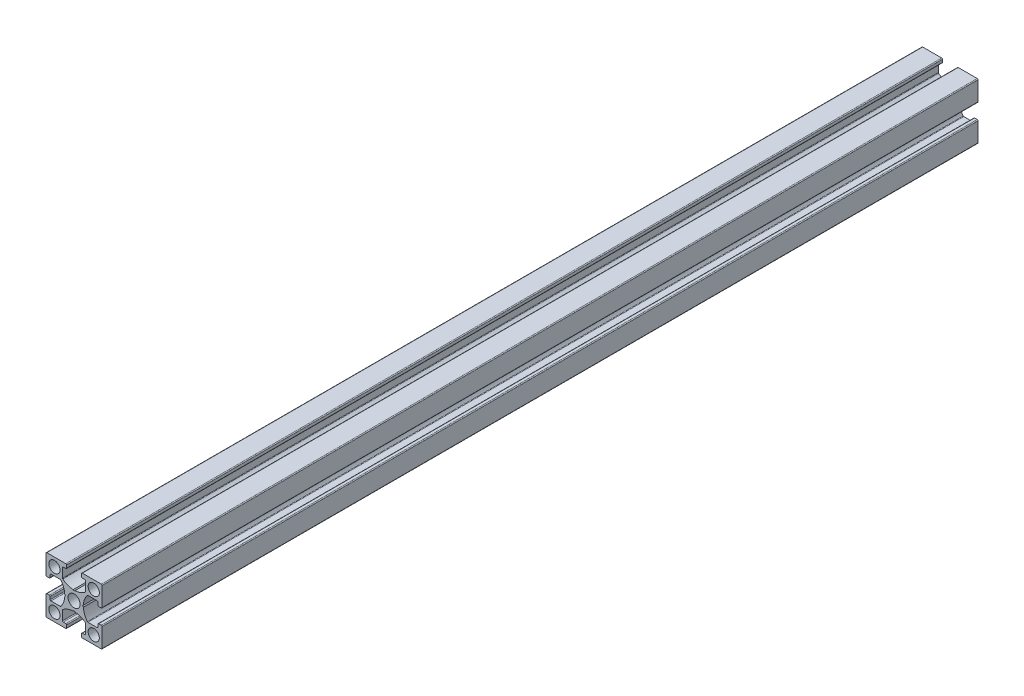
SolidWorks part; units mm, degrees
ref_plane "정면" through (0, 0, 0) normal (0, 0, 1) x (1, 0, 0)
ref_plane "윗면" through (0, 0, 0) normal (0, 1, 0) x (1, 0, 0)
ref_plane "우측면" through (0, 0, 0) normal (1, 0, 0) x (0, 0, -1)
sketch "Model" plane through (0, 0, 0) normal (0, 0, 1) x (1, 0, 0)
  line L0 (2292.4151, 1187.1915) -> (2314.8128, 1187.1915) construction
  line L1 (2307.7639, 1192.1343) -> (2307.7639, 1195.3915)
  line L2 (2307.4639, 1195.6915) -> (2306.5639, 1195.6915)
  line L3 (2306.2639, 1195.9915) -> (2306.2639, 1196.8915)
  line L4 (2306.5639, 1197.1915) -> (2313.3139, 1197.1915)
  line L5 (2313.6139, 1196.8915) -> (2313.6139, 1190.1415)
  line L6 (2313.3139, 1189.8415) -> (2312.4139, 1189.8415)
  line L7 (2312.1139, 1190.1415) -> (2312.1139, 1191.0415)
  line L8 (2311.8139, 1191.3415) -> (2308.5567, 1191.3415)
  line L9 (2306.9212, 1187.4988) -> (2306.6139, 1187.1915)
  line L10 (2306.6139, 1187.1915) -> (2306.9212, 1186.8843)
  line L11 (2308.5567, 1183.0415) -> (2311.8139, 1183.0415)
  line L12 (2312.1139, 1183.3415) -> (2312.1139, 1184.2415)
  line L13 (2312.4139, 1184.5415) -> (2313.3139, 1184.5415)
  line L14 (2313.6139, 1184.2415) -> (2313.6139, 1177.4915)
  line L15 (2313.3139, 1177.1915) -> (2306.5639, 1177.1915)
  line L16 (2306.2639, 1177.4915) -> (2306.2639, 1178.3915)
  line L17 (2306.5639, 1178.6915) -> (2307.4639, 1178.6915)
  line L18 (2307.7639, 1178.9915) -> (2307.7639, 1182.2488)
  line L19 (2303.9212, 1183.8843) -> (2303.6139, 1184.1915)
  line L20 (2303.6139, 1184.1915) -> (2303.3066, 1183.8843)
  line L21 (2299.4639, 1182.2488) -> (2299.4639, 1178.9915)
  line L22 (2299.7639, 1178.6915) -> (2300.6639, 1178.6915)
  line L23 (2300.9639, 1178.3915) -> (2300.9639, 1177.4915)
  line L24 (2300.6639, 1177.1915) -> (2293.9139, 1177.1915)
  line L25 (2293.6139, 1177.4915) -> (2293.6139, 1184.2415)
  line L26 (2293.9139, 1184.5415) -> (2294.8139, 1184.5415)
  line L27 (2295.1139, 1184.2415) -> (2295.1139, 1183.3415)
  line L28 (2295.4139, 1183.0415) -> (2298.6712, 1183.0415)
  line L29 (2300.3066, 1186.8843) -> (2300.6139, 1187.1915)
  line L30 (2300.6139, 1187.1915) -> (2300.3066, 1187.4988)
  line L31 (2298.6712, 1191.3415) -> (2295.4139, 1191.3415)
  line L32 (2295.1139, 1191.0415) -> (2295.1139, 1190.1415)
  line L33 (2294.8139, 1189.8415) -> (2293.9139, 1189.8415)
  line L34 (2293.6139, 1190.1415) -> (2293.6139, 1196.8915)
  line L35 (2293.9139, 1197.1915) -> (2300.6639, 1197.1915)
  line L36 (2300.9639, 1196.8915) -> (2300.9639, 1195.9915)
  line L37 (2300.6639, 1195.6915) -> (2299.7639, 1195.6915)
  line L38 (2299.4639, 1195.3915) -> (2299.4639, 1192.1343)
  line L39 (2303.3066, 1190.4988) -> (2303.6139, 1190.1915)
  line L40 (2303.6139, 1190.1915) -> (2303.9212, 1190.4988)
  line L41 (2294.1139, 1194.1915) -> (2299.1139, 1194.1915) construction
  line L42 (2296.6139, 1196.6915) -> (2296.6139, 1191.6915) construction
  line L43 (2294.1139, 1180.1915) -> (2299.1139, 1180.1915) construction
  line L44 (2296.6139, 1177.6915) -> (2296.6139, 1182.6915) construction
  line L45 (2303.6139, 1198.3904) -> (2303.6139, 1175.9927) construction
  line L46 (2313.1139, 1194.1915) -> (2308.1139, 1194.1915) construction
  line L47 (2310.6139, 1196.6915) -> (2310.6139, 1191.6915) construction
  line L48 (2310.6139, 1177.6915) -> (2310.6139, 1182.6915) construction
  line L49 (2313.1139, 1180.1915) -> (2308.1139, 1180.1915) construction
  circle A0 centre (2303.6139, 1187.1915) radius 2.15
  circle A1 centre (2296.6139, 1194.1915) radius 2
  circle A2 centre (2296.6139, 1180.1915) radius 2
  circle A3 centre (2310.6139, 1194.1915) radius 2
  circle A4 centre (2310.6139, 1180.1915) radius 2
  arc A5 (2307.7639, 1195.3915) -> (2307.4639, 1195.6915) centre (2307.4639, 1195.3915) ccw
  arc A6 (2306.2639, 1195.9915) -> (2306.5639, 1195.6915) centre (2306.5639, 1195.9915) ccw
  arc A7 (2306.5639, 1197.1915) -> (2306.2639, 1196.8915) centre (2306.5639, 1196.8915) ccw
  arc A8 (2313.6139, 1196.8915) -> (2313.3139, 1197.1915) centre (2313.3139, 1196.8915) ccw
  arc A9 (2313.3139, 1189.8415) -> (2313.6139, 1190.1415) centre (2313.3139, 1190.1415) ccw
  arc A10 (2312.1139, 1190.1415) -> (2312.4139, 1189.8415) centre (2312.4139, 1190.1415) ccw
  arc A11 (2312.1139, 1191.0415) -> (2311.8139, 1191.3415) centre (2311.8139, 1191.0415) ccw
  arc A12 (2308.5567, 1191.3415) -> (2308.3217, 1191.2281) centre (2308.5567, 1191.0415) ccw
  arc A13 (2308.3217, 1191.2281) -> (2306.9212, 1187.4988) centre (2313.4048, 1187.1915) ccw
  arc A14 (2306.9212, 1186.8843) -> (2308.3217, 1183.155) centre (2313.4048, 1187.1915) ccw
  arc A15 (2308.3217, 1183.155) -> (2308.5567, 1183.0415) centre (2308.5567, 1183.3415) ccw
  arc A16 (2311.8139, 1183.0415) -> (2312.1139, 1183.3415) centre (2311.8139, 1183.3415) ccw
  arc A17 (2312.4139, 1184.5415) -> (2312.1139, 1184.2415) centre (2312.4139, 1184.2415) ccw
  arc A18 (2313.6139, 1184.2415) -> (2313.3139, 1184.5415) centre (2313.3139, 1184.2415) ccw
  arc A19 (2313.3139, 1177.1915) -> (2313.6139, 1177.4915) centre (2313.3139, 1177.4915) ccw
  arc A20 (2306.2639, 1177.4915) -> (2306.5639, 1177.1915) centre (2306.5639, 1177.4915) ccw
  arc A21 (2306.5639, 1178.6915) -> (2306.2639, 1178.3915) centre (2306.5639, 1178.3915) ccw
  arc A22 (2307.4639, 1178.6915) -> (2307.7639, 1178.9915) centre (2307.4639, 1178.9915) ccw
  arc A23 (2307.7639, 1182.2488) -> (2307.6505, 1182.4837) centre (2307.4639, 1182.2488) ccw
  arc A24 (2307.6505, 1182.4837) -> (2303.9212, 1183.8843) centre (2303.6139, 1177.4007) ccw
  arc A25 (2303.3066, 1183.8843) -> (2299.5774, 1182.4837) centre (2303.6139, 1177.4007) ccw
  arc A26 (2299.5774, 1182.4837) -> (2299.4639, 1182.2488) centre (2299.7639, 1182.2488) ccw
  arc A27 (2299.4639, 1178.9915) -> (2299.7639, 1178.6915) centre (2299.7639, 1178.9915) ccw
  arc A28 (2300.9639, 1178.3915) -> (2300.6639, 1178.6915) centre (2300.6639, 1178.3915) ccw
  arc A29 (2300.6639, 1177.1915) -> (2300.9639, 1177.4915) centre (2300.6639, 1177.4915) ccw
  arc A30 (2293.6139, 1177.4915) -> (2293.9139, 1177.1915) centre (2293.9139, 1177.4915) ccw
  arc A31 (2293.9139, 1184.5415) -> (2293.6139, 1184.2415) centre (2293.9139, 1184.2415) ccw
  arc A32 (2295.1139, 1184.2415) -> (2294.8139, 1184.5415) centre (2294.8139, 1184.2415) ccw
  arc A33 (2295.1139, 1183.3415) -> (2295.4139, 1183.0415) centre (2295.4139, 1183.3415) ccw
  arc A34 (2298.6712, 1183.0415) -> (2298.9061, 1183.155) centre (2298.6712, 1183.3415) ccw
  arc A35 (2298.9061, 1183.155) -> (2300.3066, 1186.8843) centre (2293.8231, 1187.1915) ccw
  arc A36 (2300.3066, 1187.4988) -> (2298.9061, 1191.2281) centre (2293.8231, 1187.1915) ccw
  arc A37 (2298.9061, 1191.2281) -> (2298.6712, 1191.3415) centre (2298.6712, 1191.0415) ccw
  arc A38 (2295.4139, 1191.3415) -> (2295.1139, 1191.0415) centre (2295.4139, 1191.0415) ccw
  arc A39 (2294.8139, 1189.8415) -> (2295.1139, 1190.1415) centre (2294.8139, 1190.1415) ccw
  arc A40 (2293.6139, 1190.1415) -> (2293.9139, 1189.8415) centre (2293.9139, 1190.1415) ccw
  arc A41 (2293.9139, 1197.1915) -> (2293.6139, 1196.8915) centre (2293.9139, 1196.8915) ccw
  arc A42 (2300.9639, 1196.8915) -> (2300.6639, 1197.1915) centre (2300.6639, 1196.8915) ccw
  arc A43 (2300.6639, 1195.6915) -> (2300.9639, 1195.9915) centre (2300.6639, 1195.9915) ccw
  arc A44 (2299.7639, 1195.6915) -> (2299.4639, 1195.3915) centre (2299.7639, 1195.3915) ccw
  arc A45 (2299.4639, 1192.1343) -> (2299.5774, 1191.8994) centre (2299.7639, 1192.1343) ccw
  arc A46 (2299.5774, 1191.8994) -> (2303.3066, 1190.4988) centre (2303.6139, 1196.9824) ccw
  arc A47 (2303.9212, 1190.4988) -> (2307.6505, 1191.8994) centre (2303.6139, 1196.9824) ccw
  arc A48 (2307.6505, 1191.8994) -> (2307.7639, 1192.1343) centre (2307.4639, 1192.1343) ccw
extrude "보스-돌출1" add sketch "Model" along normal blind 312
